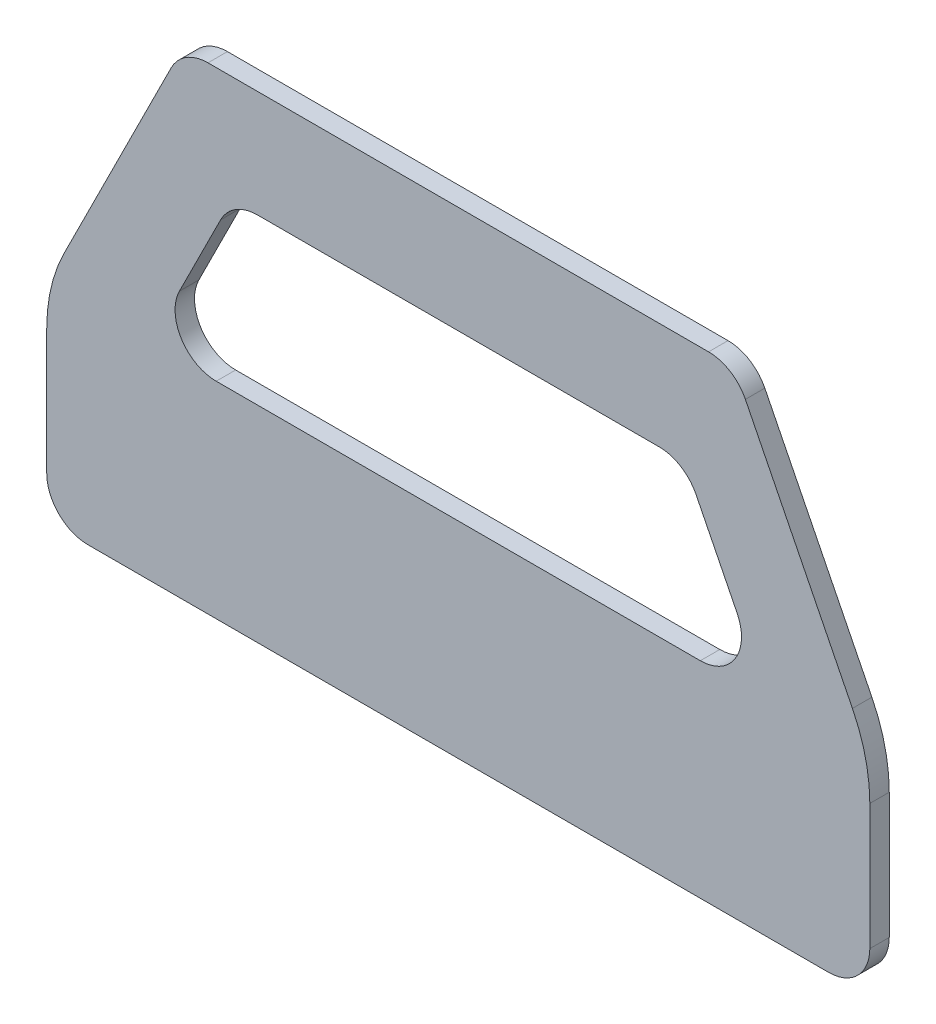
SolidWorks part; units mm, degrees
material "PC High Viscosity"
ref_plane "Front Plane" through (0, 0, 0) normal (0, 0, 1) x (1, 0, 0)
ref_plane "Top Plane" through (0, 0, 0) normal (0, 1, 0) x (1, 0, 0)
ref_plane "Right Plane" through (0, 0, 0) normal (1, 0, 0) x (0, 0, -1)
sketch "Sketch1" plane through (0, 0, 0) normal (0, 0, 1) x (1, 0, 0)
  line L0 (40.9398, 81.8796) -> (53.6398, 107.2796)
  line L1 (12.7, 0) -> (241.3, 0)
  line L2 (0, 12.7) -> (0, 51.5077)
  line L3 (52.299, 63.5) -> (201.701, 63.5)
  line L4 (254, 12.7) -> (254, 51.5077)
  line L5 (57.15, 63.5) -> (196.85, 63.5)
  line L6 (57.15, 63.5) -> (57.15, 114.3) construction
  line L7 (64.999, 114.3) -> (189.001, 114.3)
  line L8 (196.85, 63.5) -> (196.85, 114.3) construction
  line L9 (213.0602, 81.8796) -> (200.3602, 107.2796)
  line L10 (5.3631, 74.2262) -> (38.3998, 140.2996)
  line L11 (49.759, 147.32) -> (204.241, 147.32)
  line L12 (215.6002, 140.2996) -> (248.6369, 74.2262)
  line L13 (0, 63.5) -> (31.75, 63.5) construction
  line L14 (222.25, 63.5) -> (254, 63.5) construction
  arc A0 (204.241, 147.32) -> (215.6002, 140.2996) centre (204.241, 134.62) cw
  arc A1 (38.3998, 140.2996) -> (49.759, 147.32) centre (49.759, 134.62) cw
  arc A2 (189.001, 114.3) -> (200.3602, 107.2796) centre (189.001, 101.6) cw
  arc A3 (213.0602, 81.8796) -> (201.701, 63.5) centre (201.701, 76.2) cw
  arc A4 (40.9398, 81.8796) -> (52.299, 63.5) centre (52.299, 76.2) ccw
  arc A5 (53.6398, 107.2796) -> (64.999, 114.3) centre (64.999, 101.6) cw
  arc A6 (248.6369, 74.2262) -> (254, 51.5077) centre (203.2, 51.5077) cw
  arc A7 (0, 51.5077) -> (5.3631, 74.2262) centre (50.8, 51.5077) cw
  arc A8 (241.3, 0) -> (254, 12.7) centre (241.3, 12.7) ccw
  arc A9 (12.7, 0) -> (0, 12.7) centre (12.7, 12.7) cw
  point P13 (0, 0)
  point P14 (41.91, 147.32)
  point P15 (43.381, 147.32)
  point P40 (254, 0)
  point P43 (0, 0)
  dimension "D9" = 12.7
  dimension "D10" = 50.8
  dimension "D11" = 12.7
  dimension "D1" = 63.5
  dimension "D2" = 254
  dimension "D3" = 50.8
  dimension "D4" = 139.7
  dimension "D5" = 57.15
  dimension "D6" = 25.4
  dimension "D7" = 25.4
  dimension "D8" = 33.02
extrude "Boss-Extrude1" add sketch "Sketch1" along normal blind 6 contours A1 L10 L2 L1 L4 L12 A0 L11 L0 A5 L7 A2 L9 A3 L3 A4
